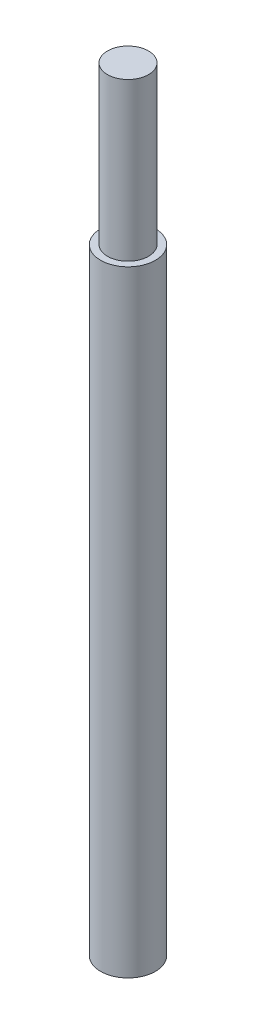
SolidWorks part; units mm, degrees
ref_plane "Front Plane" through (0, 0, 0) normal (0, 0, 1) x (1, 0, 0)
ref_plane "Top Plane" through (0, 0, 0) normal (0, 1, 0) x (1, 0, 0)
ref_plane "Right Plane" through (0, 0, 0) normal (1, 0, 0) x (0, 0, -1)
sketch "Sketch1" plane through (0, 0, 0) normal (0, 1, 0) x (1, 0, 0)
  circle A0 centre (0, 0) radius 4
  dimension "D1" = 8
extrude "Boss-Extrude1" add sketch "Sketch1" along normal blind 90
sketch "Sketch2" plane through (0, 90, 0) normal (0, 1, 0) x (1, 0, 0)
  circle A0 centre (0, 0) radius 3
  dimension "D1" = 6
extrude "Boss-Extrude2" add sketch "Sketch2" along normal blind 23
